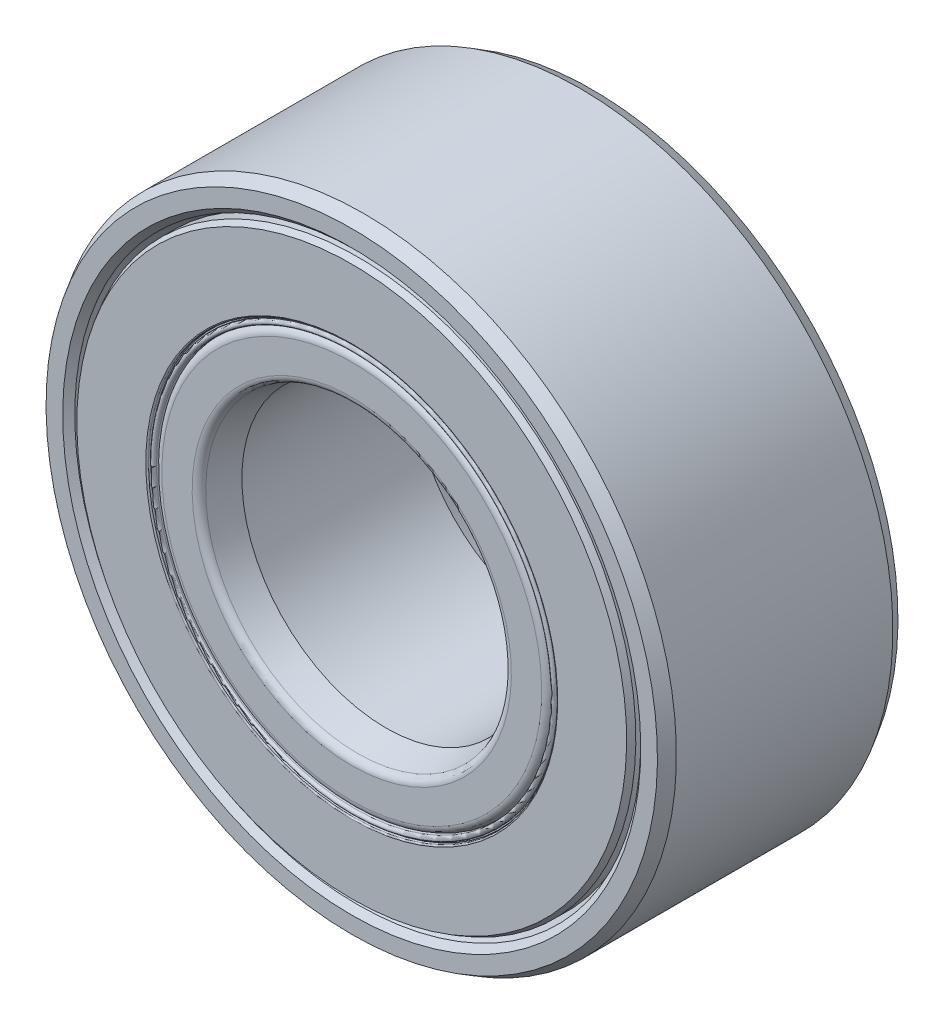
SolidWorks part; units mm, degrees
ref_plane "Front Plane" through (0, 0, 0) normal (0, 0, 1) x (1, 0, 0)
ref_plane "Top Plane" through (0, 0, 0) normal (0, 1, 0) x (1, 0, 0)
ref_plane "Right Plane" through (0, 0, 0) normal (1, 0, 0) x (0, 0, -1)
sketch "Sketch1" plane through (0, 0, 0) normal (0, 0, 1) x (1, 0, 0)
  line L0 (-6.5, 0) -> (6.5, 0) construction
  line L1 (-3, 0) -> (3, 0) construction
  circle A0 centre (0, 0) radius 3 construction
  circle A1 centre (0, 0) radius 6.5 construction
  point P3 (0, 0)
  point P6 (0, 0)
  point P7 (0, -3)
  point P11 (0, -6.5)
  point P12 (0, 3)
  point P13 (0, 6.5)
  dimension "OD" = 13
  dimension "ID" = 6
sketch "Sketch2" plane through (0, 0, 0) normal (1, 0, 0) x (0, 0, -1)
  line L0 (-2.5, 6.5) -> (2.5, 6.5) construction
  line L1 (0, 6.5) -> (0, -6.5) construction
  line L2 (2.25, 6.5) -> (-2.25, 6.5)
  line L3 (-2.25, 6.5) -> (-2.5, 6.3557)
  line L4 (-2.5, 6.3557) -> (-2.5, 6.0087)
  line L5 (-2.1037, 5.785) -> (-1.0119, 5.785)
  line L6 (2.1037, 5.785) -> (1.0119, 5.785)
  line L7 (2.5, 6.3557) -> (2.5, 6.0087)
  line L8 (2.25, 6.5) -> (2.5, 6.3557)
  line L9 (-1.0119, 5.785) -> (-1.0119, 6.0233) construction
  line L10 (-1.0119, 6.0233) -> (-1.0119, 6.2617) construction
  line L11 (0, 6.5) -> (0, -6.5) construction
  line L12 (-2.5, 0) -> (2.5, 0) construction
  line L13 (2.5, 3) -> (-2.5, 3) construction
  line L14 (-2.5, 3) -> (-2.5, -3) construction
  line L15 (-2.5, -3) -> (2.5, -3) construction
  line L16 (2.5, 6.5) -> (2.5, -6.5) construction
  line L17 (-1.0119, 6.2617) -> (-1.0119, 6.5) construction
  line L18 (-1.0119, 6.2617) -> (0, 6.2617) construction
  line L20 (-2.1037, 5.785) -> (-2.375, 5.8837)
  line L21 (-2.375, 5.8837) -> (-2.5, 6.0087)
  line L26 (2.375, 5.8837) -> (2.5, 6.0087)
  line L27 (2.1037, 5.785) -> (2.375, 5.8837)
  arc A0 (-1.0119, 5.785) -> (1.0119, 5.785) centre (0, 4.9492) cw
  circle A1 centre (0, 4.9492) radius 1.3125 construction
  point P17 (0, 0)
  point P21 (0, 6.5)
  point P30 (0, -3)
  dimension "Approx. Ball Dia." = 2.625
  dimension "Width" = 5
  dimension "For Shaft Diameter" = 6
  dimension "For Housing ID" = 13
  dimension "D4" = 11.57
  dimension "D2" = 20
  dimension "D5" = 45
  dimension "D1" = 30
  dimension "D6" = 0.25
  dimension "D7" = 0.125
sketch "Sketch3" plane through (0, 0, 0) normal (1, 0, 0) x (0, 0, -1)
  line L14 (-2.1037, 5.785) -> (-2.375, 5.8837) construction
  line L15 (-2.375, 5.8837) -> (-2.5, 6.0087) construction
  line L16 (-2.5, 6.3557) -> (-2.5, 6.0087) construction
  line L17 (-2.25, 6.5) -> (-2.5, 6.3557) construction
  line L18 (2.25, 6.5) -> (-2.25, 6.5) construction
  line L19 (2.25, 6.5) -> (2.5, 6.3557) construction
  line L20 (2.5, 6.3557) -> (2.5, 6.0087) construction
  line L21 (2.375, 5.8837) -> (2.5, 6.0087) construction
  line L22 (2.1037, 5.785) -> (2.375, 5.8837) construction
  line L23 (2.1037, 5.785) -> (1.0119, 5.785) construction
  line L24 (-2.1037, 5.785) -> (-1.0119, 5.785) construction
  line L25 (-2.1037, 5.785) -> (-2.375, 5.8837)
  line L26 (-2.375, 5.8837) -> (-2.5, 6.0087)
  line L27 (-2.5, 6.3557) -> (-2.5, 6.0087)
  line L28 (-2.25, 6.5) -> (-2.5, 6.3557)
  line L29 (2.25, 6.5) -> (-2.25, 6.5)
  line L30 (2.25, 6.5) -> (2.5, 6.3557)
  line L31 (2.5, 6.3557) -> (2.5, 6.0087)
  line L32 (2.375, 5.8837) -> (2.5, 6.0087)
  line L33 (2.1037, 5.785) -> (2.375, 5.8837)
  line L34 (2.1037, 5.785) -> (1.0119, 5.785)
  line L35 (-2.1037, 5.785) -> (-1.0119, 5.785)
  arc A2 (1.0119, 5.785) -> (-1.0119, 5.785) centre (0, 4.9492) ccw construction
  arc A3 (1.0119, 5.785) -> (-1.0119, 5.785) centre (0, 4.9492) ccw
revolve "Revolve1" add sketch "Sketch3" angle 360 about L12
sketch "Sketch4" plane through (0, 0, 0) normal (1, 0, 0) x (0, 0, -1)
  line L0 (0, 6.5) -> (0, -6.5) construction
  line L1 (0, 6.5) -> (0, -6.5) construction
  line L2 (-1.7838, 3) -> (-2.3779, 3.1592)
  line L3 (-2.5, 3.3183) -> (-2.5, 3.9486)
  line L4 (2.5, -6.3557) -> (2.5, 6.3557) construction
  line L5 (-2.3352, 4.1133) -> (-1.0119, 4.1133)
  line L6 (-1.7838, 3) -> (1.7838, 3)
  line L7 (2.5, 6.3557) -> (2.5, 6.0087) construction
  line L8 (1.7838, 3) -> (2.3779, 3.1592)
  line L9 (0, 6.2617) -> (0, 3) construction
  line L10 (2.5, 3.3183) -> (2.5, 3.9486)
  line L11 (2.3352, 4.1133) -> (1.0119, 4.1133)
  line L12 (1.7838, 3) -> (1.7838, 3.1592) construction
  line L13 (1.7838, 3.1592) -> (1.7838, 3.3183) construction
  line L14 (1.7838, 3.3183) -> (1.7838, 3.4775) construction
  line L15 (1.7838, 3.4775) -> (1.7838, 3.6367) construction
  circle A0 centre (0, 4.9492) radius 1.3125 construction
  arc A1 (1.0119, 4.1133) -> (-1.0119, 4.1133) centre (0, 4.9492) cw
  arc A2 (2.5, 3.9486) -> (2.3352, 4.1133) centre (2.3352, 3.9486) ccw
  arc A3 (-2.5, 3.9486) -> (-2.3352, 4.1133) centre (-2.3352, 3.9486) cw
  arc A4 (2.3779, 3.1592) -> (2.5, 3.3183) centre (2.3352, 3.3183) ccw
  arc A5 (-2.3779, 3.1592) -> (-2.5, 3.3183) centre (-2.3352, 3.3183) cw
  point P14 (2.5, 3.1919)
  point P36 (0, 3.6367)
  dimension "D1" = 15
revolve "Revolve2" add sketch "Sketch4" angle 360 about L12
sketch "Sketch5" plane through (0, 0, 0) normal (1, 0, 0) x (0, 0, -1)
  line L0 (-1.3125, 4.9492) -> (1.3125, 4.9492)
  arc A2 (-1.3125, 4.9492) -> (1.3125, 4.9492) centre (0, 4.9492) cw
  arc A3 (1.0119, 5.785) -> (-1.0119, 5.785) centre (0, 4.9492) ccw construction
revolve "Revolve3" add sketch "Sketch5" angle 360 about L0
pattern_circular "CirPattern1" count 9 over 360 about axis through (0, 0, 0) along (0, 0, 1) of bodies 104
sketch "Sketch6" plane through (0, 0, 0) normal (1, 0, 0) x (0, 0, -1)
  line L1 (-2.3788, 5.785) -> (-1.3125, 5.785)
  line L2 (-2.5, 5.715) -> (-2.5, 4.2813)
  line L3 (-2.472, 4.2533) -> (-1.3125, 4.2533)
  line L4 (-1.3125, 5.785) -> (-1.3125, 4.2533)
  line L5 (-2.5, 3.3183) -> (-2.5, 3.9486) construction
  line L6 (-2.25, 6.5) -> (-2.5, 6.3557) construction
  line L7 (0, 6.5) -> (0, 3) construction
  line L8 (2.472, 4.2533) -> (1.3125, 4.2533)
  line L9 (1.3125, 5.785) -> (1.3125, 4.2533)
  line L10 (2.3788, 5.785) -> (1.3125, 5.785)
  line L11 (2.5, 5.715) -> (2.5, 4.2813)
  line L13 (-2.3352, 4.1133) -> (-1.0119, 4.1133) construction
  line L14 (-2.5, 5.715) -> (-2.3788, 5.785)
  line L15 (-2.1037, 5.785) -> (-1.0119, 5.785) construction
  line L16 (2.5, 5.715) -> (2.3788, 5.785)
  arc A0 (-2.5, 4.2813) -> (-2.472, 4.2533) centre (-2.472, 4.2813) ccw
  circle A1 centre (0, 4.9492) radius 1.3125 construction
  arc A2 (2.5, 4.2813) -> (2.472, 4.2533) centre (2.472, 4.2813) cw
  point P26 (-2.5, 4.2533)
  dimension "D3" = 0.028
  dimension "D1" = 0.14
revolve "Revolve4" add sketch "Sketch6" angle 360 about L12
sketch "Sketch7" plane through (0, 0, 0) normal (1, 0, 0) x (0, 0, -1)
  line L3 (-1.3125, 4.2533) -> (-2.3906, 4.2533)
  line L4 (-2.472, 4.2533) -> (-1.3125, 4.2533) construction
  line L7 (0, 3.6367) -> (0, 3) construction
  line L8 (0, 6.5) -> (0, -6.5) construction
  line L21 (-2.3906, 4.2533) -> (-2.425, 4.2473)
  line L22 (-2.4225, 4.2183) -> (-2.4475, 4.2183)
  line L23 (-2.4475, 4.1133) -> (-1.3125, 4.1133)
  line L24 (-1.3125, 4.1133) -> (-1.3125, 4.2533)
  line L25 (-2.3352, 4.1133) -> (-1.0119, 4.1133) construction
  line L26 (-2.5, 4.2813) -> (-2.5, 4.1133) construction
  line L27 (-2.5, 4.1133) -> (-2.4475, 4.1133) construction
  line L28 (-2.3906, 4.2533) -> (-2.3906, 4.2183) construction
  line L29 (-2.3906, 4.2183) -> (-2.3906, 4.1833) construction
  line L30 (-2.3906, 4.1833) -> (-2.3906, 4.1483) construction
  line L31 (-2.3906, 4.1483) -> (-2.3906, 4.1133) construction
  circle A2 centre (0, 4.9492) radius 1.3125 construction
  arc A9 (-2.425, 4.2473) -> (-2.4225, 4.2183) centre (-2.4225, 4.2329) ccw
  arc A10 (-2.4475, 4.2183) -> (-2.4475, 4.1133) centre (-2.4475, 4.1658) ccw
  dimension "D1" = 0.025
  dimension "D2" = 10
revolve "Revolve5" add sketch "Sketch7" angle 360 about L12
equation "\"D4@Sketch2\"=\"OD@Sketch1\"*.89"
equation "\"D1@Sketch6\"=(\"OD@Sketch1\"-\"ID@Sketch1\")*.02"
equation "\"D2@Sketch6\"=\"D1@Sketch6\"*.5"
equation "\"D3@Sketch6\"=\"D1@Sketch6\"*.2"
equation "\"D6@Sketch2\"=\"Width@Sketch2\"*.05"
equation "\"D7@Sketch2\"=\"D6@Sketch2\"*.5"
equation "\"D1@CirPattern1\" =  ( pi * \"OD@Sketch1\" )  * .5625 / \"Approx. Ball Dia.@Sketch2\""
equation "\"Approx. Ball Dia.@Sketch2\"=(\"OD@Sketch1\"-\"ID@Sketch1\")*.5*.75"
